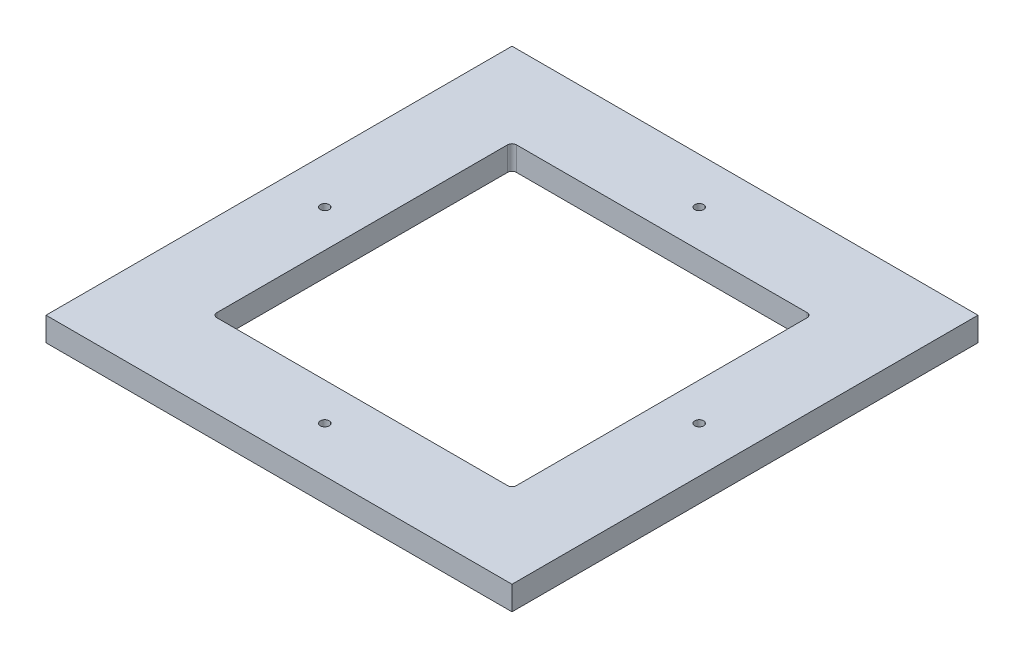
SolidWorks part; units mm, degrees
material "Pine"
ref_plane "Front Plane" through (0, 0, 0) normal (0, 0, 1) x (1, 0, 0)
ref_plane "Top Plane" through (0, 0, 0) normal (0, 1, 0) x (1, 0, 0)
ref_plane "Right Plane" through (0, 0, 0) normal (1, 0, 0) x (0, 0, -1)
sketch "Sketch1" plane through (0, 0, 0) normal (0, 1, 0) x (1, 0, 0)
  line L1 (-177.8, 177.8) -> (177.8, 177.8)
  line L2 (-177.8, 177.8) -> (-177.8, -177.8)
  line L3 (-177.8, -177.8) -> (177.8, -177.8)
  line L4 (177.8, 177.8) -> (177.8, -177.8)
  line L5 (0, -177.8) -> (0, 177.8) construction
  line L6 (-177.8, 0) -> (177.8, 0) construction
  point P0 (0, 0)
  dimension "D1" = 355.6
extrude "Boss-Extrude1" add sketch "Sketch1" along normal blind 18.2562
sketch "Sketch3" plane through (0, 18.2562, 0) normal (0, 1, 0) x (1, 0, 0)
  line L0 (0, -142.875) -> (0, 142.875) construction
  line L1 (-142.875, 0) -> (142.875, 0) construction
  point P4 (0, 0)
  point P8 (0, 0)
  dimension "D1" = 285.75
hole_wizard "1/4 Clearance Hole1" positions "Sketch4" profile "Sketch5" hole size "1/4" standard "ANSI Inch" end condition up to next
sketch "Sketch4" plane through (0, 18.2562, 0) normal (0, 1, 0) x (1, 0, 0)
  point P0 (0, 142.875)
  point P3 (-142.875, 0)
  point P6 (0, -142.875)
  point P9 (142.875, 0)
sketch "Sketch5" plane through (0, 18.2562, -142.875) normal (1, 0, 0) x (0, 0, 1)
  line L0 (0, 0) -> (0, 18.2562)
  line L1 (0, 18.2562) -> (3.3782, 18.2562)
  line L2 (3.3782, 18.2562) -> (3.3782, 0)
  line L5 (3.3782, 0) -> (0, 0)
  line L11 (0, -6.35) -> (0, 107.95) construction
  dimension "Thru Hole Dia." = 6.7564
  dimension "Thru Hole Depth" = 18.2562
sketch "Sketch8" plane through (0, 18.2562, 0) normal (0, 1, 0) x (1, 0, 0)
  line L0 (177.8, 177.8) -> (-177.8, 177.8) construction
  line L1 (114.3, -114.3) -> (-114.3, -114.3)
  line L2 (114.3, -114.3) -> (114.3, 114.3)
  line L3 (114.3, 114.3) -> (-114.3, 114.3)
  line L4 (-114.3, -114.3) -> (-114.3, 114.3)
  line L5 (114.3, -114.3) -> (-114.3, 114.3) construction
  line L6 (114.3, 114.3) -> (-114.3, -114.3) construction
  point P0 (0, 0)
  dimension "D1" = 63.5
extrude "Cut-Extrude3" cut sketch "Sketch8" against normal through all
fillet "Fillet2" radius 3.3782 4 edges at (114.3, 9.1281, -114.3) (114.3, 9.1281, 114.3) (-114.3, 9.1281, -114.3) (-114.3, 9.1281, 114.3)
